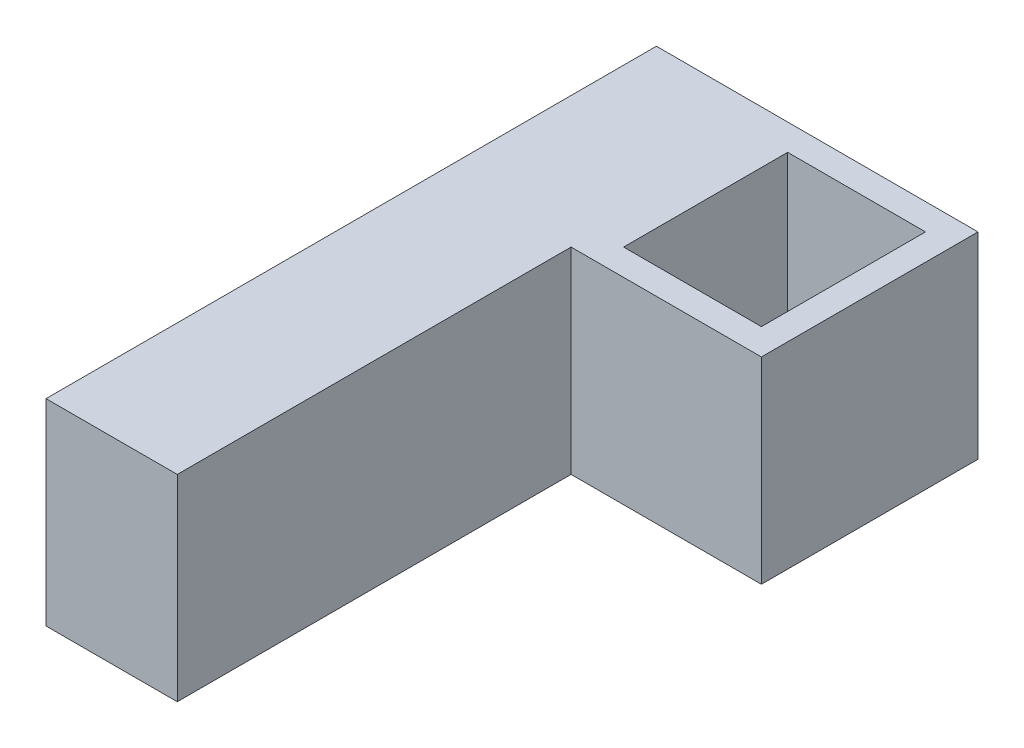
SolidWorks part; units mm, degrees
ref_plane "Front Plane" through (0, 0, 0) normal (0, 0, 1) x (1, 0, 0)
ref_plane "Top Plane" through (0, 0, 0) normal (0, 1, 0) x (1, 0, 0)
ref_plane "Right Plane" through (0, 0, 0) normal (1, 0, 0) x (0, 0, -1)
sketch "Sketch2" plane through (0, 0, 0) normal (0, 1, 0) x (1, 0, 0)
  line L1 (0, 0) -> (10.5, 0)
  line L2 (0, 0) -> (0, -12.5)
  line L3 (0, -12.5) -> (10.5, -12.5)
  line L4 (10.5, 0) -> (10.5, -12.5)
  line L5 (-2, -14.5) -> (12.5, -14.5)
  line L6 (12.5, 2) -> (12.5, -14.5)
  line L7 (-2, 2) -> (12.5, 2)
  line L8 (-12, -14.5) -> (-12, -44.5)
  line L9 (-2, -14.5) -> (-2, -44.5)
  line L10 (-2, 2) -> (-12, 2)
  line L11 (-12, 2) -> (-12, -14.5)
  line L12 (-2, -44.5) -> (-12, -44.5)
  line L13 (-2, 2) -> (-2, -14.5) construction
  dimension "D1" = 10.5
  dimension "D2" = 12.5
  dimension "D4" = 30
  dimension "D5" = 10
  dimension "D3" = 2
extrude "Boss-Extrude1" add sketch "Sketch2" along normal blind 15
